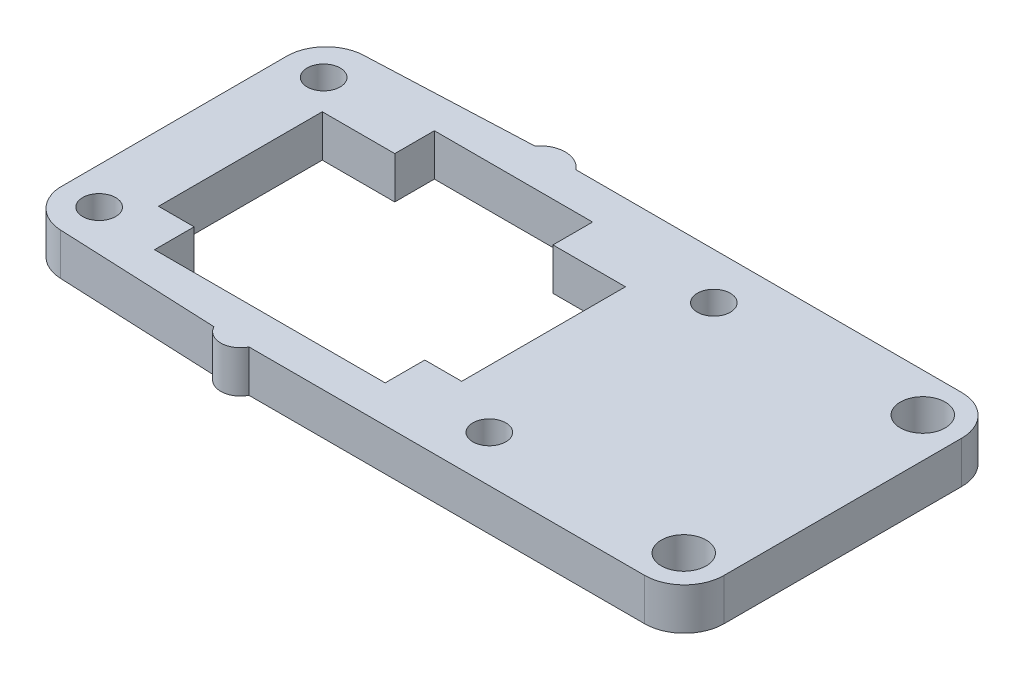
SolidWorks part; units mm, degrees
material "Acrylic (Medium-high impact)"
ref_plane "Front Plane" through (0, 0, 0) normal (0, 0, 1) x (1, 0, 0)
ref_plane "Top Plane" through (0, 0, 0) normal (0, 1, 0) x (1, 0, 0)
ref_plane "Right Plane" through (0, 0, 0) normal (1, 0, 0) x (0, 0, -1)
sketch "Sketch1" plane through (0, 0, 0) normal (0, 1, 0) x (1, 0, 0)
  line L0 (-11.458, 17.8403) -> (-8.8126, 17.8403) construction
  line L1 (-11.458, 0.8397) -> (-8.8126, 0.8397) construction
  line L2 (18.0895, 0.8397) -> (20.7349, 0.8395) construction
  line L3 (18.0895, 17.8403) -> (20.7349, 17.8401) construction
  line L4 (33.188, 0.2898) -> (36.1825, 0.2896) construction
  line L5 (33.1878, 18.3903) -> (36.1827, 18.3903) construction
  line L16 (12.2751, 3.1399) -> (12.2251, 3.1399)
  line L17 (12.2251, 3.1399) -> (12.2251, 0.1398)
  line L18 (12.2251, 0.1398) -> (-5.2438, 0.1398)
  line L19 (-5.2438, 0.1398) -> (-5.2438, 3.1399)
  line L20 (-5.2438, 3.1399) -> (-7.939, 3.1399)
  line L21 (-7.939, 3.1399) -> (-7.939, 15.5403)
  line L22 (-7.939, 15.5403) -> (-2.4489, 15.5403)
  line L23 (-2.4489, 15.5403) -> (-2.4489, 18.5403)
  line L24 (-2.4489, 18.5403) -> (9.5301, 18.5403)
  line L25 (9.5301, 18.5403) -> (9.5301, 15.5403)
  line L26 (9.5301, 15.5403) -> (15.0202, 15.5403)
  line L27 (15.0202, 15.5403) -> (15.0202, 3.1399)
  line L28 (15.0202, 3.1399) -> (12.2751, 3.1399)
  line L29 (4.7092, -2.6602) -> (34.6802, -2.6602)
  line L30 (37.6801, 0.3397) -> (37.6801, 18.3457)
  line L31 (2.35, 21.3404) -> (-10.0923, 20.8081)
  line L32 (-12.9301, 17.8121) -> (-12.9161, 0.5756)
  line L33 (-10.0923, -2.128) -> (2.0595, -2.6602)
  arc A0 (2.0595, -2.6602) -> (4.7092, -2.6602) centre (3.3843, -1.9843) ccw
  arc A1 (2.35, 21.3404) -> (5.4575, 21.3404) centre (3.9038, 20.1508) cw
  arc A2 (34.6853, 21.3404) -> (37.6801, 18.3457) centre (34.6853, 18.3457) cw
  arc A3 (37.6801, 0.3397) -> (34.6802, -2.6602) centre (34.6802, 0.3397) cw
  arc A4 (-10.0923, -2.128) -> (-12.9161, 0.5756) centre (-9.9625, 0.8341) cw
  arc A5 (-10.0923, 20.8081) -> (-12.9301, 17.8121) centre (-9.9655, 17.846) ccw
  circle A6 centre (-10.1353, 17.8403) radius 1.25
  circle A7 centre (-10.1353, 0.8397) radius 1.25
  circle A8 centre (19.4122, 0.8396) radius 1.25
  circle A9 centre (19.4122, 17.8402) radius 1.25
  circle A10 centre (34.6852, 0.2897) radius 1.7
  circle A11 centre (34.6853, 18.3903) radius 1.7
  spline S13 degree 2 poles (34.6853, 21.3404) (13.556, 21.3404) (5.4575, 21.3404) knots 8 8 8 9 9 9
  dimension "D1" = 2.5
  dimension "D2" = 3.4
extrude "Boss-Extrude1" add sketch "Sketch1" along normal blind 3.175
